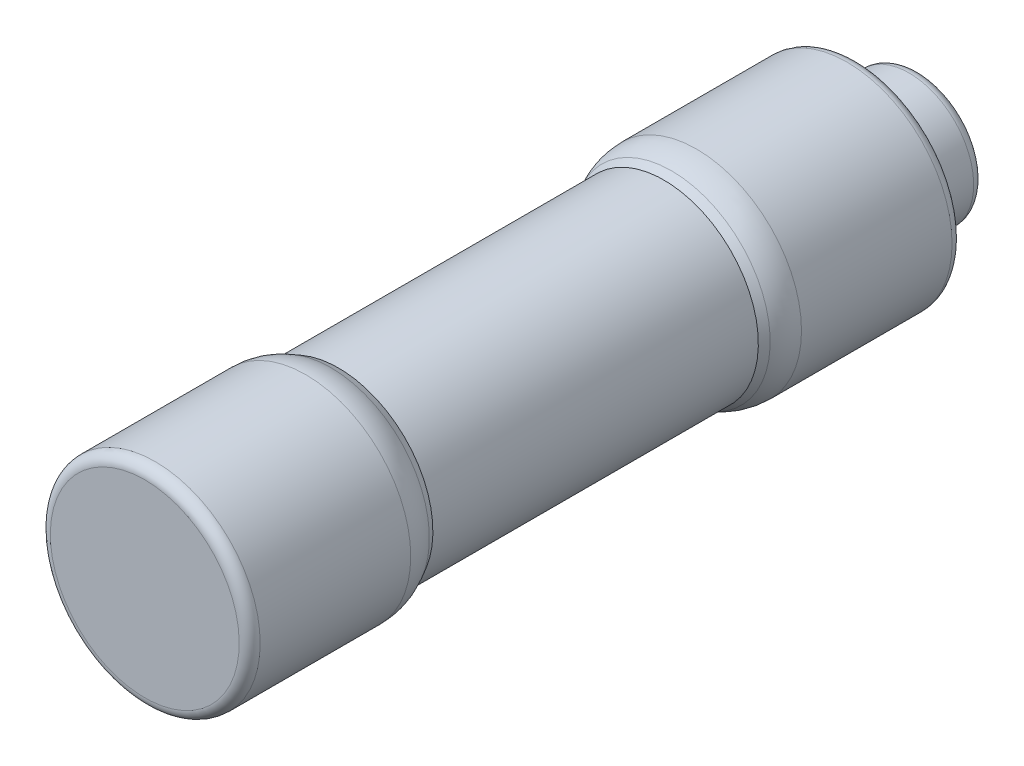
SolidWorks part; units mm, degrees
ref_plane "Front Plane" through (0, 0, 0) normal (0, 0, 1) x (1, 0, 0)
ref_plane "Top Plane" through (0, 0, 0) normal (0, 1, 0) x (1, 0, 0)
ref_plane "Right Plane" through (0, 0, 0) normal (1, 0, 0) x (0, 0, -1)
sketch "Sketch1" plane through (0, 0, 0) normal (1, 0, 0) x (0, 0, -1)
  line L0 (-19.05, 0) -> (19.05, 0) construction
  line L1 (-19.05, 5.1594) -> (-19.05, -5.1594) construction
  line L2 (19.05, -3.175) -> (19.05, 3.175) construction
  line L3 (16.002, -3.175) -> (16.002, 3.175) construction
  point P2 (0, 0)
  point P6 (-19.05, 0)
  point P7 (6.477, 0)
  point P8 (-9.525, 0)
  point P12 (19.05, 0)
  point P15 (16.002, 0)
  dimension "Overall Length" = 38.1
  dimension "Overall Diameter" = 10.3187
  dimension "D1" = 9.525
  dimension "Rejection End Length" = 3.048
  dimension "Rejection End OD" = 6.35
  dimension "D2" = 9.525
sketch "Sketch2" plane through (0, 0, 0) normal (1, 0, 0) x (0, 0, -1)
  line L0 (-19.05, 5.1594) -> (-19.05, 0)
  line L5 (6.477, 4.6434) -> (-9.525, 4.6434)
  line L6 (-9.525, 4.6434) -> (-10.4775, 5.1594)
  line L7 (-10.4775, 5.1594) -> (-19.05, 5.1594)
  line L8 (-19.05, 0) -> (19.05, 0)
  line L9 (-19.05, 0) -> (19.05, 0) construction
  line L10 (19.05, 0) -> (19.05, 3.175)
  line L11 (19.05, 3.175) -> (16.002, 3.175)
  line L12 (16.002, 3.175) -> (16.002, 5.1594)
  line L13 (16.002, 5.1594) -> (7.4295, 5.1594)
  line L14 (7.4295, 5.1594) -> (6.477, 4.6434)
  dimension "D1" = 9.2869
  dimension "D2" = 0.9525
  dimension "D3" = 0.9525
revolve "Revolve1" add sketch "Sketch2" angle 360 about L9
fillet "Fillet2" radius 2.5797 2 edges at (0, -5.1594, 10.4775) (0, -5.1594, -7.4295)
fillet "Fillet1" radius 0.5159 4 edges at (0, -5.1594, 19.05) (0, -3.175, -19.05) (0, -3.175, -16.002) (0, -5.1594, -16.002)
sketch "Sketch3" plane through (0, 0, 0) normal (1, 0, 0) x (0, 0, -1)
  line L0 (-9.525, -4.6434) -> (-9.525, 4.6434) construction
  line L1 (6.477, -4.6434) -> (6.477, 4.6434) construction
  line L2 (-9.525, -4.6434) -> (-9.525, 4.6434)
  line L3 (6.477, -4.6434) -> (6.477, 4.6434)
  line L4 (-9.525, -4.6434) -> (6.477, -4.6434)
split "Split1" trim tools "Sketch3" bodies to split 104 resulting bodies 105 106 107
ref_point "EndPoint"
equation "\"D1@Sketch2\" = \"Overall Diameter@Sketch1\" * .9"
equation "\"D2@Sketch2\"=\"Overall Length@Sketch1\" * .025"
equation "\"D1@Fillet2\"=\"Overall Diameter@Sketch1\" * .25"
equation "\"D1@Sketch1\"=\"Overall Length@Sketch1\"/4"
equation "\"D2@Sketch1\"=\"D1@Sketch1\""
equation "\"D3@Sketch2\"=\"D2@Sketch2\""
equation "\"D1@Fillet1\"=\"Overall Diameter@Sketch1\"/20"
